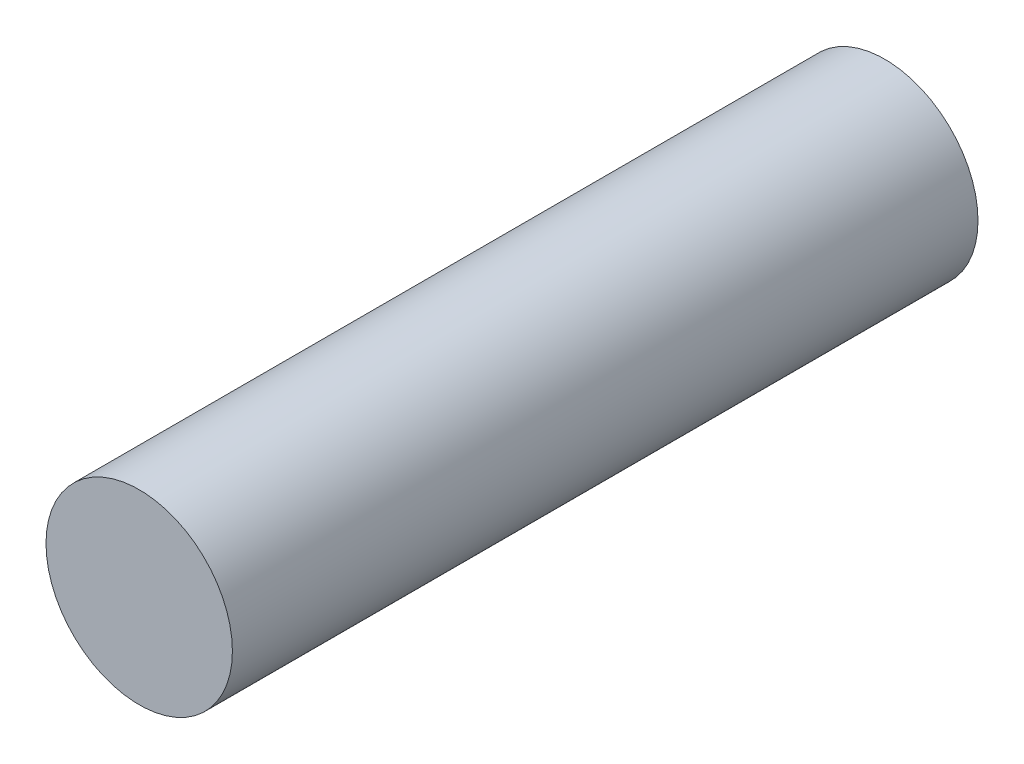
SolidWorks part; units mm, degrees
ref_plane "Front Plane" through (0, 0, 0) normal (0, 0, 1) x (1, 0, 0)
ref_plane "Top Plane" through (0, 0, 0) normal (0, 1, 0) x (1, 0, 0)
ref_plane "Right Plane" through (0, 0, 0) normal (1, 0, 0) x (0, 0, -1)
sketch "Sketch1" plane through (0, 0, 0) normal (0, 0, 1) x (1, 0, 0)
  circle A0 centre (0, 0) radius 6.35
  dimension "D1" = 12.7
extrude "Boss-Extrude1" add sketch "Sketch1" along normal blind 50.8 contours A0
ref_plane "Plane1" through (0, 0, 9.525) normal (0, 0, 1) x (1, 0, 0)
ref_plane "Plane2" through (0, 0, 19.05) normal (0, 0, 1) x (1, 0, 0)
